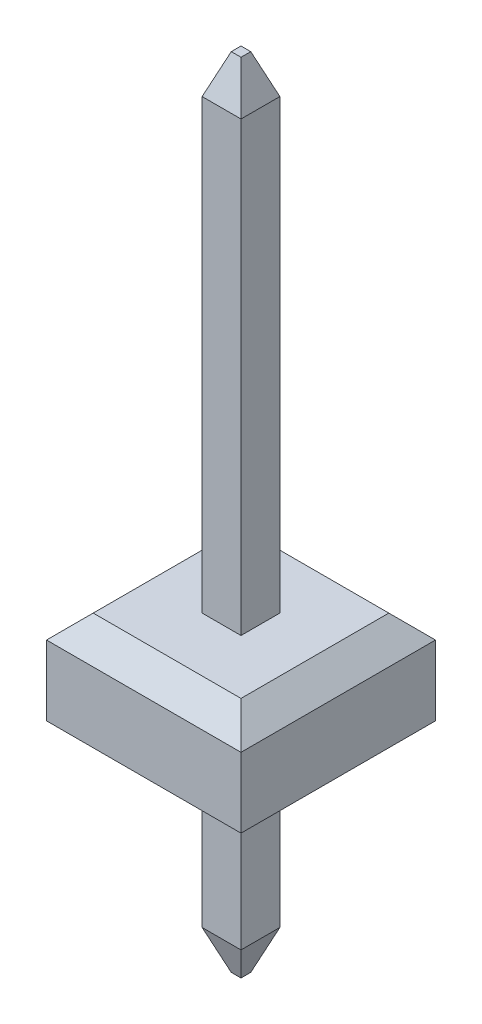
SolidWorks part; units mm, degrees
ref_plane "Front Plane" through (0, 0, 0) normal (0, 0, 1) x (1, 0, 0)
ref_plane "Top Plane" through (0, 0, 0) normal (0, 1, 0) x (1, 0, 0)
ref_plane "Right Plane" through (0, 0, 0) normal (1, 0, 0) x (0, 0, -1)
sketch "Sketch1" plane through (0, 0, 0) normal (0, 1, 0) x (1, 0, 0)
  line L1 (0, 0) -> (2.54, 0)
  line L2 (0, 0) -> (0, 2.54)
  line L3 (0, 2.54) -> (2.54, 2.54)
  line L4 (2.54, 0) -> (2.54, 2.54)
  dimension "D1" = 2.54
  dimension "D2" = 2.54
extrude "Boss-Extrude1" add sketch "Sketch1" along normal blind 1.524
sketch "Sketch2" plane through (0, 1.524, 0) normal (0, 1, 0) x (1, 0, 0)
  line L0 (0, 2.54) -> (0, 0) construction
  line L1 (0, 0) -> (2.54, 0) construction
  line L2 (1.27, 0) -> (1.27, 2.0363) construction
  line L3 (1.524, 1.524) -> (1.016, 1.524)
  line L4 (1.524, 1.524) -> (1.524, 1.016)
  line L5 (1.524, 1.016) -> (1.016, 1.016)
  line L6 (1.016, 1.524) -> (1.016, 1.016)
  line L7 (1.524, 1.524) -> (1.016, 1.016) construction
  line L8 (1.524, 1.016) -> (1.016, 1.524) construction
  line L9 (0, 1.27) -> (2.1183, 1.27) construction
  point P0 (0, 1.27)
  point P1 (1.27, 0)
  point P4 (1.27, 1.27)
  point P7 (1.27, 1.27)
  dimension "D1" = 0.508
  dimension "D2" = 0.508
  dimension "D3" = 0
  dimension "D4" = 0
extrude "Boss-Extrude2" add sketch "Sketch2" along normal blind 6.35
sketch "Sketch3" plane through (0, 0, 0) normal (0, -1, 0) x (1, 0, 0)
  line L4 (1.016, -1.016) -> (1.016, -1.524)
  line L5 (1.524, -1.016) -> (1.016, -1.016)
  line L6 (1.524, -1.524) -> (1.524, -1.016)
  line L7 (1.016, -1.524) -> (1.524, -1.524)
  line L8 (1.016, -1.016) -> (1.016, -1.524)
  line L9 (1.524, -1.016) -> (1.016, -1.016)
  line L10 (1.524, -1.524) -> (1.524, -1.016)
  line L11 (1.016, -1.524) -> (1.524, -1.524)
  dimension "D1" = 0
extrude "Boss-Extrude3" add sketch "Sketch3" along normal blind 2.54
chamfer "Chamfer1" distance 0.508 distance2 0.1905 4 edges at (1.524, 7.874, -1.27) (1.27, 7.874, -1.524) (1.016, 7.874, -1.27) (1.27, 7.874, -1.016)
chamfer "Chamfer2" distance 0.508 distance2 0.1905 4 edges at (1.524, -2.54, -1.27) (1.27, -2.54, -1.524) (1.016, -2.54, -1.27) (1.27, -2.54, -1.016)
chamfer "Chamfer4" distance 0.3048 angle 45 4 edges at (2.54, 1.524, -1.27) (1.27, 1.524, -2.54) (0, 1.524, -1.27) (1.27, 1.524, 0)
chamfer "Chamfer5" distance 0.3048 angle 45 4 edges at (2.54, 0, -1.27) (1.27, 0, -2.54) (0, 0, -1.27) (1.27, 0, 0)
